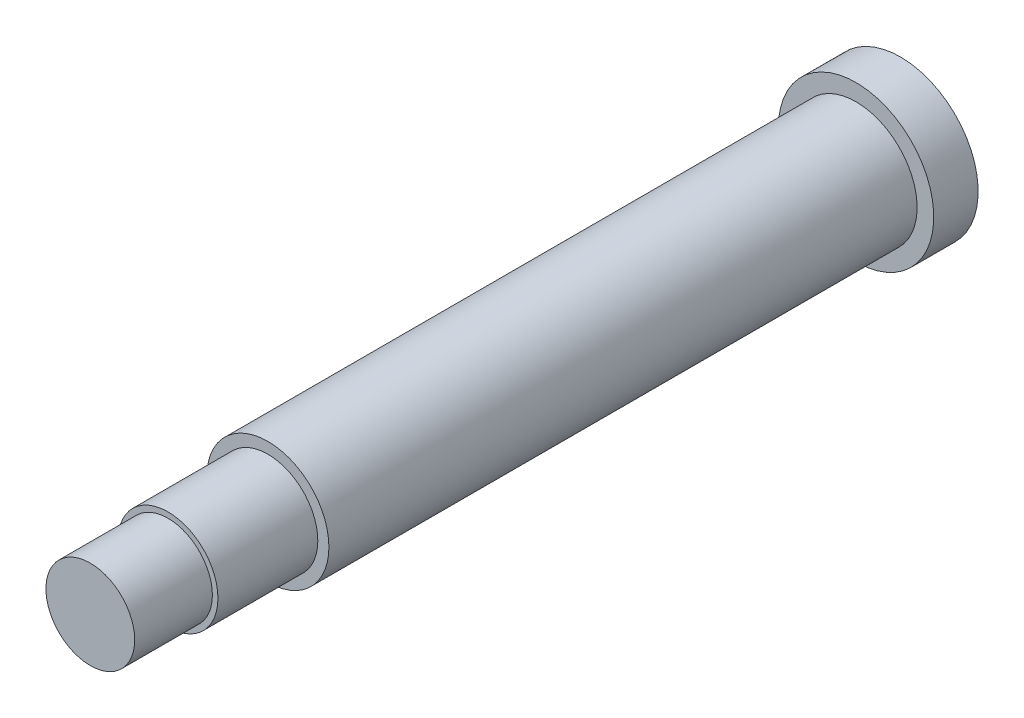
SolidWorks part; units mm, degrees
ref_plane "Front Plane" through (0, 0, 0) normal (0, 0, 1) x (1, 0, 0)
ref_plane "Top Plane" through (0, 0, 0) normal (0, 1, 0) x (1, 0, 0)
ref_plane "Right Plane" through (0, 0, 0) normal (1, 0, 0) x (0, 0, -1)
sketch "Sketch1" plane through (0, 0, 0) normal (0, 0, 1) x (1, 0, 0)
  circle A0 centre (0, 0) radius 5.5
  dimension "D1" = 11
extrude "Extrude1" add sketch "Sketch1" along normal blind 66
sketch "Sketch3" plane through (0, 0, 66) normal (0, 0, 1) x (1, 0, 0)
  circle A0 centre (0, 0) radius 4.5
  circle A1 centre (0, 0) radius 5.5
  dimension "D1" = 9
  dimension "D2" = 11
extrude "Extrude2" cut sketch "Sketch3" against normal blind 9
sketch "Sketch4" plane through (0, 0, 0) normal (0, 0, -1) x (-1, 0, 0)
  circle A0 centre (0, 0) radius 7
  dimension "D1" = 14
extrude "Extrude3" add sketch "Sketch4" against normal blind 4
sketch "Sketch5" plane through (0, 0, 66) normal (0, 0, 1) x (1, 0, 0)
  circle A0 centre (0, 0) radius 4
  dimension "D1" = 8
extrude "Extrude4" add sketch "Sketch5" along normal blind 7
